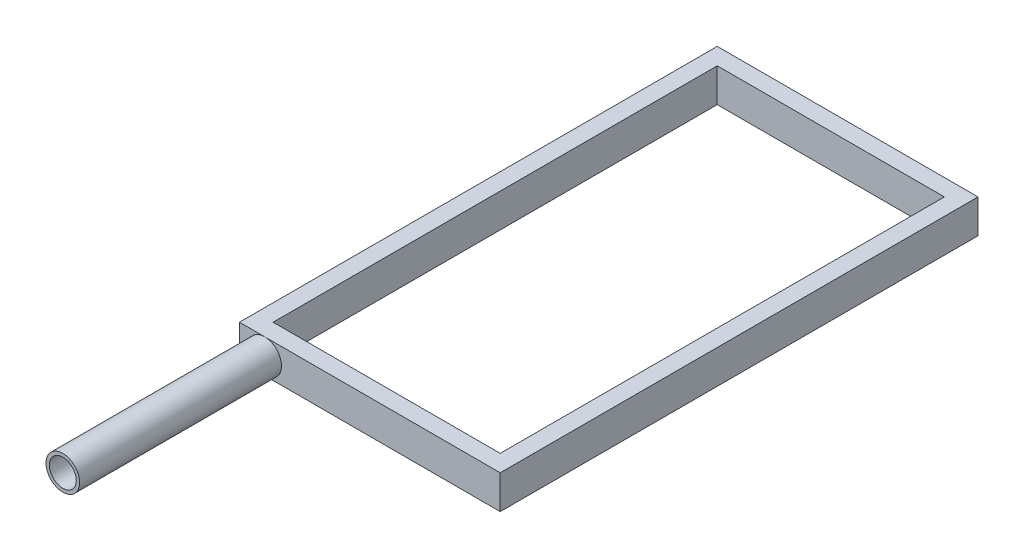
SolidWorks part; units mm, degrees
material "C40 or 38NiCrMo4"
ref_plane "Piano frontale" through (0, 0, 0) normal (0, 0, 1) x (1, 0, 0)
ref_plane "Piano superiore" through (0, 0, 0) normal (0, 1, 0) x (1, 0, 0)
ref_plane "Piano destro" through (0, 0, 0) normal (1, 0, 0) x (0, 0, -1)
sketch "Schizzo1" plane through (0, 0, 0) normal (0, 1, 0) x (1, 0, 0)
  line L1 (0, 0) -> (135, 0)
  line L2 (0, 0) -> (0, 264)
  line L3 (0, 264) -> (135, 264)
  line L4 (135, 0) -> (135, 264)
  dimension "D1" = 264
  dimension "D2" = 135
extrude "Estrusione-Sottile1" add sketch "Schizzo1" along normal blind 20 thin
sketch "Schizzo2" plane through (0, 0, 10) normal (0, 0, 1) x (1, 0, 0)
  line L0 (-10, 10) -> (27.5162, 10) construction
  line L1 (-10, 20) -> (-10, 0) construction
  circle A0 centre (5, 10) radius 10
  circle A1 centre (5, 10) radius 8
  dimension "D1" = 20
  dimension "D3" = 16
  dimension "D2" = 15
extrude "Estrusione-Estrusione1" add sketch "Schizzo2" along normal blind 120
